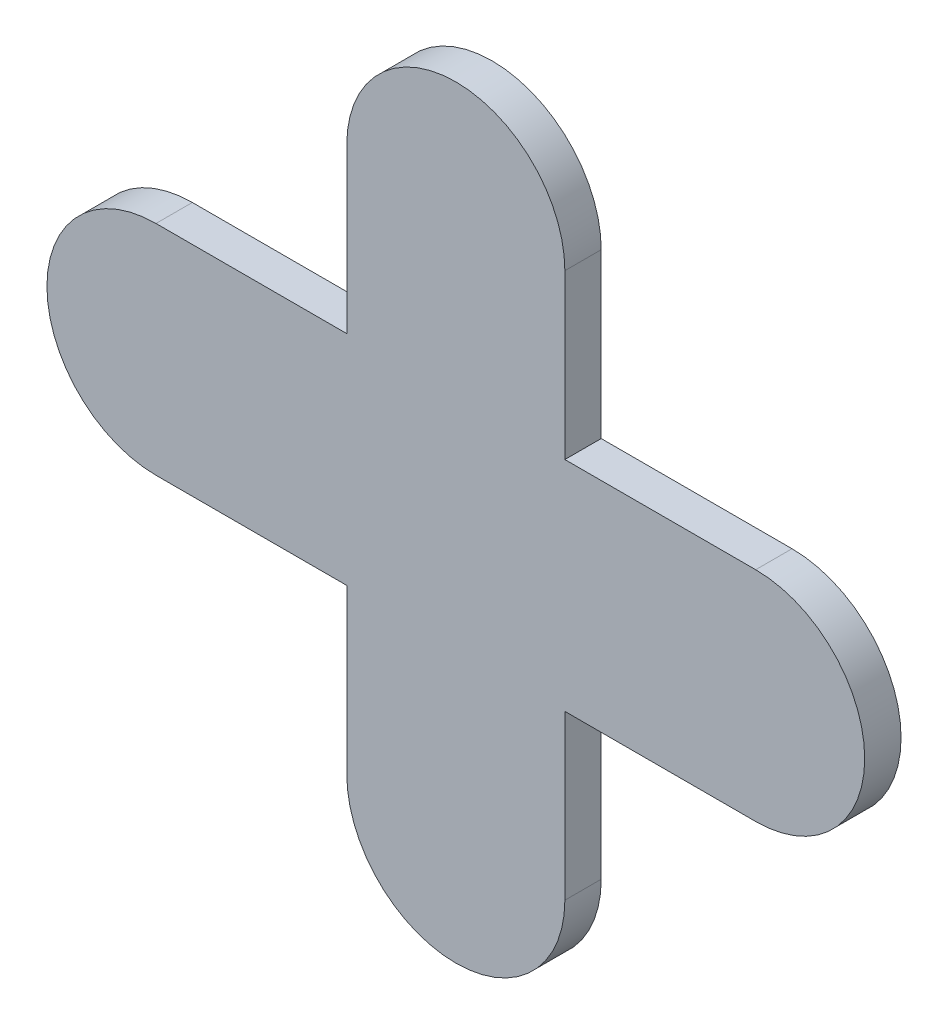
SolidWorks part; units mm, degrees
ref_plane "Plan de face" through (0, 0, 0) normal (0, 0, 1) x (1, 0, 0)
ref_plane "Plan de dessus" through (0, 0, 0) normal (0, 1, 0) x (1, 0, 0)
ref_plane "Plan de droite" through (0, 0, 0) normal (1, 0, 0) x (0, 0, -1)
sketch "Esquisse1" plane through (0, 0, 0) normal (0, 0, 1) x (1, 0, 0)
  line L0 (-16.5, 0) -> (16.5, 0) construction
  line L1 (-16.5, 6) -> (16.5, 6)
  line L2 (-16.5, -6) -> (16.5, -6)
  line L3 (0, -15) -> (0, 15) construction
  line L4 (-6, -15) -> (-6, 15)
  line L5 (6, -15) -> (6, 15)
  arc A0 (-16.5, 6) -> (-16.5, -6) centre (-16.5, 0) ccw
  arc A1 (16.5, -6) -> (16.5, 6) centre (16.5, 0) ccw
  arc A2 (-6, -15) -> (6, -15) centre (0, -15) ccw
  arc A3 (6, 15) -> (-6, 15) centre (0, 15) ccw
  point P2 (0, 0)
  point P10 (0, 0)
  dimension "D1" = 12
  dimension "D2" = 33
  dimension "D3" = 12
  dimension "D4" = 30
extrude "Boss.-Extru.1" add sketch "Esquisse1" along normal blind 2 contours L2 A1 L1 L5 | L2 L5 L1 L4 | L5 A3 L4 L1 | L1 A0 L2 L4 | L4 A2 L5 L2
sketch "Esquisse2" plane through (0, 0, 0) normal (0, 0, -1) x (-1, 0, 0)
  circle A0 centre (0, 0) radius 5
  dimension "D1" = 10
extrude "Boss.-Extru.2" add sketch "Esquisse2" along normal blind 2
sketch "Esquisse3" plane through (0, 0, -2) normal (0, 0, -1) x (-1, 0, 0)
  circle A0 centre (0, 0) radius 2.5
  dimension "D1" = 5
extrude "Enlèv. mat.-Extru.1" cut sketch "Esquisse3" against normal blind 2
